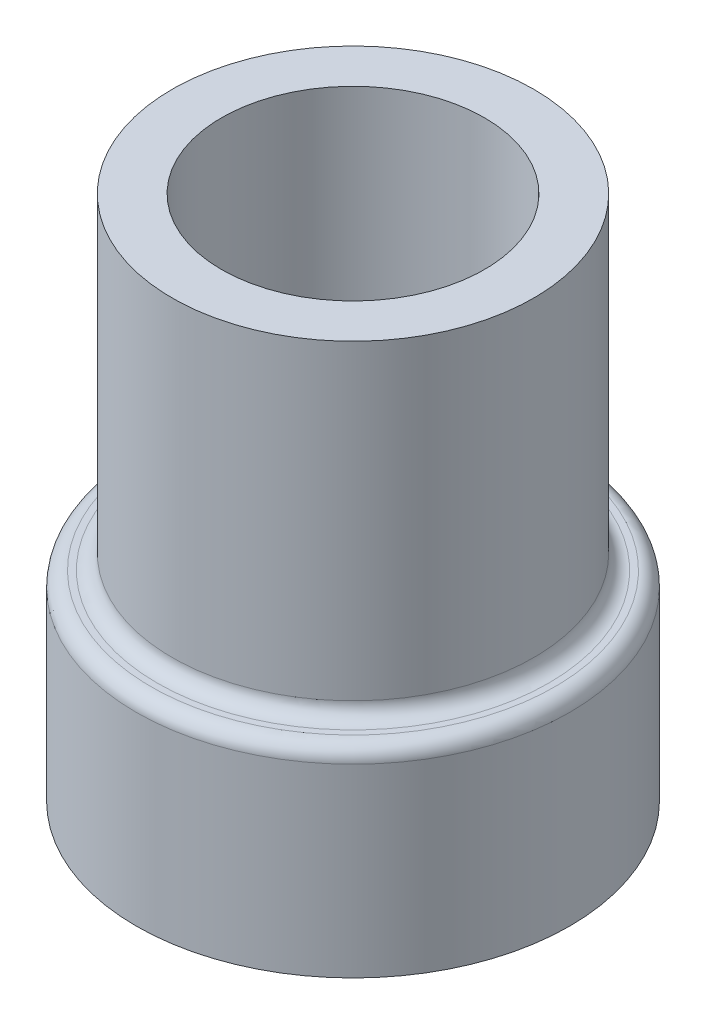
SolidWorks part; units mm, degrees
material "Silicon Rubber"
ref_plane "Front Plane" through (0, 0, 0) normal (0, 0, 1) x (1, 0, 0)
ref_plane "Top Plane" through (0, 0, 0) normal (0, 1, 0) x (1, 0, 0)
ref_plane "Right Plane" through (0, 0, 0) normal (1, 0, 0) x (0, 0, -1)
sketch "Sketch1" plane through (0, 0, 0) normal (0, 0, 1) x (1, 0, 0)
  line L0 (-13.335, 20.2692) -> (13.335, 20.2692)
  line L1 (-20.471, 20.2692) -> (-19.835, 20.2692)
  line L2 (-21.971, 18.7692) -> (-21.971, 0)
  line L3 (-21.971, 0) -> (21.971, 0)
  line L4 (21.971, 18.7692) -> (21.971, 0)
  line L5 (-13.335, 20.2692) -> (13.335, 20.2692)
  line L6 (-18.335, 21.7692) -> (-18.335, 53.34)
  line L7 (-18.335, 53.34) -> (-13.335, 53.34)
  line L8 (18.335, 21.7692) -> (18.335, 53.34)
  line L10 (-13.335, 53.34) -> (-13.335, 20.2692)
  line L11 (-13.335, 20.2692) -> (13.335, 20.2692)
  line L12 (13.335, 53.34) -> (13.335, 20.2692)
  line L13 (19.835, 20.2692) -> (20.471, 20.2692)
  line L14 (13.335, 53.34) -> (18.335, 53.34)
  line L15 (0, 0) -> (0, 53.34) construction
  arc A0 (-19.835, 20.2692) -> (-18.335, 21.7692) centre (-19.835, 21.7692) ccw
  arc A1 (-20.471, 20.2692) -> (-21.971, 18.7692) centre (-20.471, 18.7692) ccw
  arc A2 (20.471, 20.2692) -> (21.971, 18.7692) centre (20.471, 18.7692) cw
  arc A3 (19.835, 20.2692) -> (18.335, 21.7692) centre (19.835, 21.7692) cw
  point P4 (0, 0)
  point P10 (0, 20.2692)
  point P15 (0, 0)
  point P22 (21.971, 20.2692)
  point P25 (18.335, 20.2692)
  dimension "D7" = 1.5
  dimension "D1" = 43.942
  dimension "D2" = 20.2692
  dimension "D3" = 33.0708
  dimension "D4" = 5
  dimension "D5" = 5
  dimension "D6" = 26.67
revolve "Revolve1" add sketch "Sketch1" angle 360 about L15
